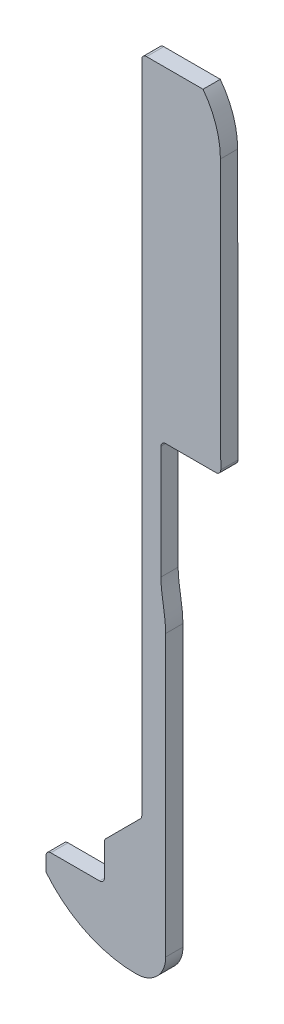
SolidWorks part; units mm, degrees
ref_plane "Płaszczyzna przednia" through (0, 0, 0) normal (0, 0, 1) x (1, 0, 0)
ref_plane "Płaszczyzna górna" through (0, 0, 0) normal (0, 1, 0) x (1, 0, 0)
ref_plane "Płaszczyzna prawa" through (0, 0, 0) normal (1, 0, 0) x (0, 0, -1)
sketch "Sketch1" plane through (0, 0, 0) normal (0, 0, 1) x (1, 0, 0)
  line L0 (0, 4.5) -> (0, 6.5)
  line L1 (0, 0) -> (18.25, 0) construction
  line L2 (0, 0) -> (0, 83.5) construction
  line L3 (0, 83.5) -> (18.25, 83.5) construction
  line L4 (18.25, 0) -> (18.25, 83.5) construction
  line L5 (0, 6.5) -> (6.1, 6.5)
  line L6 (6.1, 6.5) -> (6.1, 10.5)
  line L7 (6.1, 10.5) -> (10, 14.4)
  line L8 (10, 14.4) -> (10, 83.5)
  line L9 (10, 83.5) -> (16.4, 83.5)
  line L10 (18.2123, 78.0955) -> (18.25, 49.5)
  line L11 (18.25, 49.5) -> (12, 49.5)
  line L12 (12, 49.5) -> (12, 37.18)
  line L13 (12, 35.24) -> (12, 39.1406) construction
  line L14 (12.5, 32.33) -> (12.5, 3.07)
  line L15 (12.5, 31.0162) -> (12.5, 33.6438) construction
  arc A0 (16.4, 83.5) -> (18.2123, 78.0955) centre (9.2123, 78.0836) cw
  arc A1 (12.5, 3.07) -> (9.43, 0) centre (9.43, 3.07) cw
  arc A2 (9.43, 0) -> (0, 4.5) centre (9.43, 12.1305) cw
  spline S0 degree 3 poles (12, 37.18) (12, 35.5548) (12.5, 33.9723) (12.5, 32.33) knots 0 0 0 0 1 1 1 1
  point P5 (16.4, 83.5)
  point P6 (0, 6.5)
  point P7 (0, 4.5)
  point P8 (18.25, 49.5)
  dimension "D11" = 9
  dimension "D1" = 83.5
  dimension "D2" = 18.25
  dimension "D3" = 1.85
  dimension "D4" = 34
  dimension "D5" = 4.5
  dimension "D6" = 2
  dimension "D7" = 6.1
  dimension "D8" = 4
  dimension "D9" = 45
  dimension "D10" = 3.9
  dimension "D12" = 6.25
  dimension "D13" = 12.32
  dimension "D14" = 29.26
  dimension "D15" = 4.85
extrude "Boss-Extrude1" add sketch "Sketch1" along normal blind 1.8
fillet "Fillet1" radius 0.5 7 edges at (0, 6.5, 0.9) (6.1, 6.5, 0.9) (6.1, 10.5, 0.9) (10, 14.4, 0.9) (18.25, 49.5, 0.9) (10, 83.5, 0.9) (12, 49.5, 0.9)
